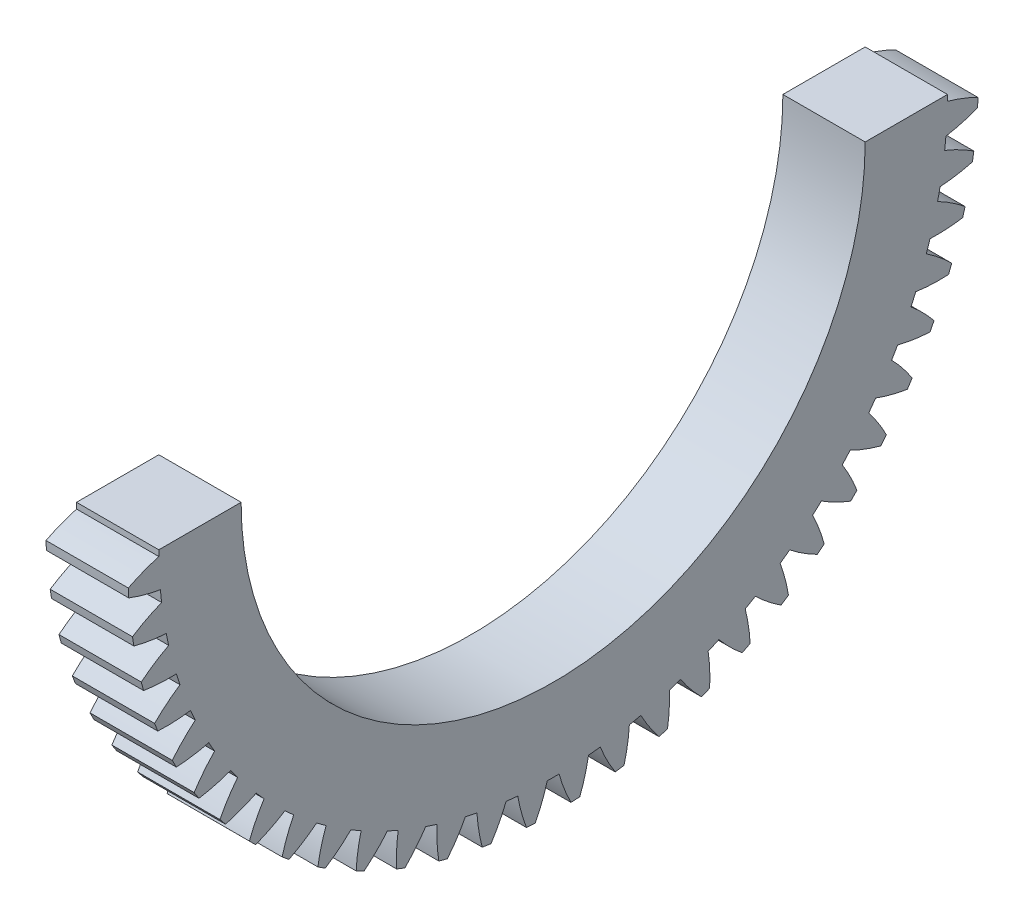
SolidWorks part; units mm, degrees
ref_plane "Plane1" through (0, 0, 0) normal (0, 0, 1) x (1, 0, 0)
ref_plane "Plane2" through (0, 0, 0) normal (0, 1, 0) x (1, 0, 0)
ref_plane "Plane3" through (0, 0, 0) normal (1, 0, 0) x (0, 0, -1)
sketch "HoldingSke" plane through (0, 0, 0) normal (0, 1, 0) x (1, 0, 0)
  line L0 (0, 0) -> (1, -1.7321)
  line L1 (-15, 0) -> (100, 0) construction
  line L2 (0, 0) -> (-2.1039, 2.3779)
  line L3 (0, 0) -> (-11.863, 4.5341)
  line L4 (0, 0) -> (4.318, 7.479)
  line L5 (0, 0) -> (-46.8476, -17.4728)
  line L6 (0, 0) -> (-2.4869, -1.6779)
  line L7 (-2.1039, 2.3779) -> (8.6586, 51.2059)
  line L8 (-76.2, 54.61) -> (-72.9, 54.61)
  line L9 (-71.009, 38.7566) -> (-53.1078, 45.2721)
  line L10 (-76.2, 71.12) -> (104.1128, 71.12)
  line L11 (0, 0) -> (-3, 0)
  line L12 (-76.2, 101.6) -> (-76.181, 101.6)
  line L13 (24.9733, 27.94) -> (52.9518, 28.4284)
  line L14 (24.9733, 27.94) -> (24.9743, 27.94)
  line L15 (24.9733, 27.94) -> (100.4006, 29.5858)
  line L16 (-63.627, -0.5) -> (-12.827, -0.5)
  circle A0 centre (0, 0) radius 13
  circle A1 centre (0, 0) radius 14.374
  circle A2 centre (0, 0) radius 37.5
  circle A3 centre (0, 0) radius 13
  dimension "MHD" = 28.748
  dimension "Hub_dia" = 75
  dimension "Bore" = 26
  dimension "MBD" = 26
  dimension "Num_teeth" = 60
  dimension "Pitch" = 2
  dimension "Overall_len" = 50
  dimension "Show_teeth" = 60
  dimension "Thickness" = 3
  dimension "OAL" = 50.0001
  dimension "T_dim" = 3.3
  dimension "Ap" = 20
  dimension "H" = 19.05
  dimension "Pitch_radius" = 180.3128
  dimension "Width" = 3
  dimension "Backlash" = 0.019
  dimension "Addendum_fac" = 1
  dimension "Dedendum_fac" = 1.25
  dimension "Clearance_fac" = 0.25
  dimension "Dedendum_add" = 0.001
  dimension "Module" = 0.5
sketch "BasProSke" plane through (0, 0, 0) normal (0, 1, 0) x (1, 0, 0)
  line L0 (-10, 0) -> (60, 0) construction
  line L1 (0, 0) -> (0, 15.5)
  line L2 (0, 0) -> (3, 0)
  line L3 (3, 0) -> (3, 15.5)
  line L4 (3, 15.5) -> (0, 15.5)
  dimension "Thickness" = 3
  dimension "Diameter" = 31
revolve "Base-Revolve" add sketch "BasProSke" angle 360 about L0
sketch "TooCutSke" plane through (0, 0, 0) normal (1, 0, 0) x (0, 0, -1)
  line L1 (0, 0) -> (0, 107) construction
  line L2 (0, 0) -> (-0.4259, 14.994) construction
  line L3 (0, 0) -> (-1.5696, 29.9503) construction
  line L4 (-0.4259, 14.994) -> (-0.7848, 14.9751) construction
  arc A0 (0.2149, 14.3724) -> (-0.2149, 14.3724) centre (0, 0) ccw
  arc A1 (0.6627, 15.5112) -> (-0.6627, 15.5112) centre (0, 0) ccw
  circle A2 centre (0, 0) radius 15 construction
  circle A3 centre (0, 0) radius 14.0954 construction
  arc A4 (-0.2149, 14.3724) -> (-0.6627, 15.5112) centre (-5.9936, 12.7576) ccw
  arc A5 (0.6627, 15.5112) -> (0.2149, 14.3724) centre (5.9936, 12.7576) ccw
  dimension "Root_dia" = 28.748
  dimension "Overcut_dia" = 31.0508
  dimension "Pitch_dia" = 30
  dimension "Base_dia" = 28.1908
  dimension "Flank_rad" = 6
  dimension "Half_ang" = 3
  dimension "Half_CT" = 0.3594
extrude "ToothCut" cut sketch "TooCutSke" along normal through all
fillet "Breaks" [suppressed] radius 0.01
fillet "RootFillets" [suppressed] radius 0.126
pattern_circular "TeethCuts" count 60 every 6 about axis through (-10, 0, 0) along (1, 0, 0) of "ToothCut", "RootFillets", "Breaks"
sketch "HubNeaOneSke" plane through (0, 0, 0) normal (-1, 0, 0) x (0, 0, 1)
  circle A0 centre (0, 0) radius 14.374
  dimension "Diameter" = 28.748
extrude "HubNearOne" [suppressed] add sketch "HubNeaOneSke" along normal blind 47.0001
sketch "HubNeaBotSke" plane through (0, 0, 0) normal (-1, 0, 0) x (0, 0, 1)
  circle A0 centre (0, 0) radius 14.374
  dimension "Diameter" = 28.748
extrude "HubNearBoth" [suppressed] add sketch "HubNeaBotSke" along normal blind 23.5
ref_plane "FarPln" through (3, 0, 0) normal (1, 0, 0) x (0, 0, -1)
sketch "HubFarSke" plane through (3, 0, 0) normal (1, 0, 0) x (0, 0, -1)
  circle A0 centre (0, 0) radius 14.374
  dimension "Diameter" = 28.748
extrude "HubFar" [suppressed] add sketch "HubFarSke" along normal blind 23.5
sketch "BorSke" plane through (0, 0, 0) normal (1, 0, 0) x (0, 0, -1)
  circle A0 centre (0, 0) radius 13
  dimension "Diameter" = 26
extrude "Bore" cut sketch "BorSke" along normal mid plane 100.0001
sketch "KeySke" plane through (0, 0, 0) normal (1, 0, 0) x (0, 0, -1)
  line L0 (-4, 0) -> (-4, 16.3)
  line L1 (-4, 16.3) -> (4, 16.3)
  line L2 (4, 16.3) -> (4, 0)
  line L3 (0, 0) -> (0, 34) construction
  line L4 (-4, 0) -> (4, 0)
  dimension "Offset" = 16.3
  dimension "Width" = 8
extrude "Keyway" [suppressed] cut sketch "KeySke" along normal mid plane 100.0001
pattern_circular "Keyway2" [suppressed] count 2 every 90 about axis through (-10, 0, 0) along (1, 0, 0)
sketch "Croquis1" plane through (3, 0, 0) normal (1, 0, 0) x (0, 0, -1)
  line L1 (-17.2606, 0) -> (17.8277, 0)
  line L2 (-17.2606, 0) -> (-17.2606, 16.2534)
  line L3 (-17.2606, 16.2534) -> (17.8277, 16.2534)
  line L4 (17.8277, 0) -> (17.8277, 16.2534)
extrude "Cortar-Extruir1" cut sketch "Croquis1" against normal through all
sketch "Croquis2" plane through (3, 0, 0) normal (1, 0, 0) x (0, 0, -1)
  line L0 (-13, 0) -> (-11.374, 0)
  line L1 (-14.374, 0) -> (-13, 0) construction
  line L2 (11.374, 0) -> (13, 0)
  line L3 (-13, -1.626) -> (11.2572, -1.626) construction
  line L4 (-13, 0) -> (13, 0) construction
  arc A0 (13, 0) -> (-13, 0) centre (0, 0) cw
  arc A1 (11.374, 0) -> (-11.374, 0) centre (0, 0) cw
  arc A2 (11.2572, -1.626) -> (-11.374, 0) centre (0, 0) cw construction
  dimension "D1" = 3
extrude "Saliente-Extruir1" add sketch "Croquis2" against normal through all
equation "' \"Module@HoldingSke\" = 6.35"
equation "' \"Num_teeth@HoldingSke\" = 12"
equation "' \"Ap@HoldingSke\" =  20"
equation "' \"Ap@HoldingSke\" = 20"
equation "' \"Width@HoldingSke\" = 0.5 * 25.4"
equation "' \"Hub_dia@HoldingSke\"= 1 * 25.4"
equation "' \"Hub_dia@HoldingSke\" = 1 * 25.4"
equation "' \"Overall_len@HoldingSke\" = 1.0 * 25.4"
equation "' \"Bore@HoldingSke\" = 0.75 * 25.4"
equation "' \"T_dim@HoldingSke\" = 0.1 * 25.4"
equation "' \"Width@KeySke\" = 0.25 * 25.4"
equation "' \"Show_teeth@HoldingSke\" = 13"
equation "' \"Backlash@HoldingSke\" = 0.009 * 25.4"
equation "' \"Addendum_fac@HoldingSke\" = 1.0"
equation "' \"Dedendum_fac@HoldingSke\" = 1.25"
equation "' \"Dedendum_add@HoldingSke\" = 0.00005 * 25.4"
equation "' \"Clearance_fac@HoldingSke\" = 0.25"
equation "\"Pitch@HoldingSke\" = 1 / \"Module@HoldingSke\""
equation "\"Overcut_dia@TooCutSke\" = (\"Num_teeth@HoldingSke\" + 2 * \"Addendum_fac@HoldingSke\") / \"Pitch@HoldingSke\" + 0.002 * 25.4"
equation "\"Pitch_dia@TooCutSke\" = \"Num_teeth@HoldingSke\" / \"Pitch@HoldingSke\""
equation "\"Base_dia@TooCutSke\" = \"Num_teeth@HoldingSke\" / \"Pitch@HoldingSke\" * cos((\"Ap@HoldingSke\"  * 3.14159265 / 180))"
equation "\"Root_dia@TooCutSke\" = (\"Num_teeth@HoldingSke\" + 2) / \"Pitch@HoldingSke\" - 2 * (\"Addendum_fac@HoldingSke\" + \"Dedendum_fac@HoldingSke\") / \"Pitch@HoldingSke\" - \"Dedendum_add@HoldingSke\" * 2"
equation "\"Half_ang@TooCutSke\" = 180 / \"Num_teeth@HoldingSke\""
equation "\"Half_CT@TooCutSke\" = \"Num_teeth@HoldingSke\" / \"Pitch@HoldingSke\" * sin((3.14159265 / 2 / \"Num_teeth@HoldingSke\")) / 2 - 7 * \"Backlash@HoldingSke\" / 4"
equation "\"Flank_rad@TooCutSke\" = \"Num_teeth@HoldingSke\" / \"Pitch@HoldingSke\" / 5"
equation "\"Radius@RootFillets\" = \"Clearance_fac@HoldingSke\" / \"Pitch@HoldingSke\" + \"Dedendum_add@HoldingSke\""
equation "\"Break_rad@Breaks\" = 0.02 / \"Pitch@HoldingSke\""
equation "\"Thickness@HoldingSke\" = \"Width@HoldingSke\""
equation "\"OAL@HoldingSke\" = \"Thickness@HoldingSke\""
equation "\"MHD@HoldingSke\" = (\"Num_teeth@HoldingSke\" + 2) / \"Pitch@HoldingSke\" - 2 * (\"Addendum_fac@HoldingSke\" + \"Dedendum_fac@HoldingSke\")  / \"Pitch@HoldingSke\" - \"Dedendum_add@HoldingSke\" * 2"
equation "\"MBD@HoldingSke\" = (\"Num_teeth@HoldingSke\" + 2) / \"Pitch@HoldingSke\" - 2 * (\"Addendum_fac@HoldingSke\" + \"Dedendum_fac@HoldingSke\")  / \"Pitch@HoldingSke\" - \"Dedendum_add@HoldingSke\" * 2 - 0.002 * 25.4"
equation "\"MHD@HoldingSke\" = ((sgn( \"MHD@HoldingSke\" - \"Hub_dia@HoldingSke\" )-1)*( \"MHD@HoldingSke\" - \"Hub_dia@HoldingSke\" ))/-2+ \"Hub_dia@HoldingSke\""
equation "\"MBD@HoldingSke\" = ((sgn( \"MBD@HoldingSke\" - \"Bore@HoldingSke\" )-1)*( \"MBD@HoldingSke\" - \"Bore@HoldingSke\" ))/-2+ \"Bore@HoldingSke\""
equation "\"OAL@HoldingSke\" = ((sgn( \"OAL@HoldingSke\" - \"Overall_len@HoldingSke\" )+1)*( \"OAL@HoldingSke\" - \"Overall_len@HoldingSke\" ))/2 + \"Overall_len@HoldingSke\" + 0.000002 * 25.4"
equation "\"Num_teeth@TeethCuts\" = int( \"Show_teeth@HoldingSke\" ) + 1"
equation "\"Num_teeth@TeethCuts\" = ((sgn( \"Num_teeth@TeethCuts\" - \"Num_teeth@HoldingSke\" )-1)*( \"Num_teeth@TeethCuts\" - \"Num_teeth@HoldingSke\" ))/-2+ \"Num_teeth@HoldingSke\""
equation "\"Num_teeth@TeethCuts\" = ((sgn( \"Num_teeth@TeethCuts\" - 2.0)+1)*( \"Num_teeth@TeethCuts\" - 2.0))/2 +2.0"
equation "\"Angle@TeethCuts\" = 360.0 / \"Num_teeth@HoldingSke\""
equation "\"Diameter@BasProSke\" = (\"Num_teeth@HoldingSke\" + 2 * \"Addendum_fac@HoldingSke\") / \"Pitch@HoldingSke\""
equation "\"Thickness@BasProSke\"  = \"Thickness@HoldingSke\""
equation "' \"Fillet_rad@BasProSke\" =  \"Thickness@HoldingSke\" * 0.05"
equation "' \"Fillet_rad@BasProSke\" = \"Thickness@HoldingSke\" * 0.05"
equation "\"MHD@HoldingSke\" = ((sgn( \"MHD@HoldingSke\" - \"Root_dia@TooCutSke\" )-1)*( \"MHD@HoldingSke\" - \"Root_dia@TooCutSke\" ))/-2+ \"Root_dia@TooCutSke\""
equation "\"Diameter@HubNeaOneSke\" = \"MHD@HoldingSke\""
equation "\"Length@HubNearOne\" = \"OAL@HoldingSke\" - \"Thickness@BasProSke\""
equation "\"Diameter@HubNeaBotSke\" = \"MHD@HoldingSke\""
equation "\"Length@HubNearBoth\" = ( \"OAL@HoldingSke\" - \"Thickness@BasProSke\" ) / 2.0"
equation "\"Thickness@FarPln\" = \"Thickness@BasProSke\""
equation "\"Diameter@HubFarSke\" = \"MHD@HoldingSke\""
equation "\"Length@HubFar\" = ( \"OAL@HoldingSke\" - \"Thickness@BasProSke\" ) / 2.0"
equation "\"Diameter@BorSke\" = \"MBD@HoldingSke\""
equation "\"D1@Bore\" = \"OAL@HoldingSke\" * 2.0"
equation "\"D1@Keyway\" = \"OAL@HoldingSke\" * 2.0"
equation "\"Offset@KeySke\" = \"T_dim@HoldingSke\" + \"MBD@HoldingSke\" / 2.0"
